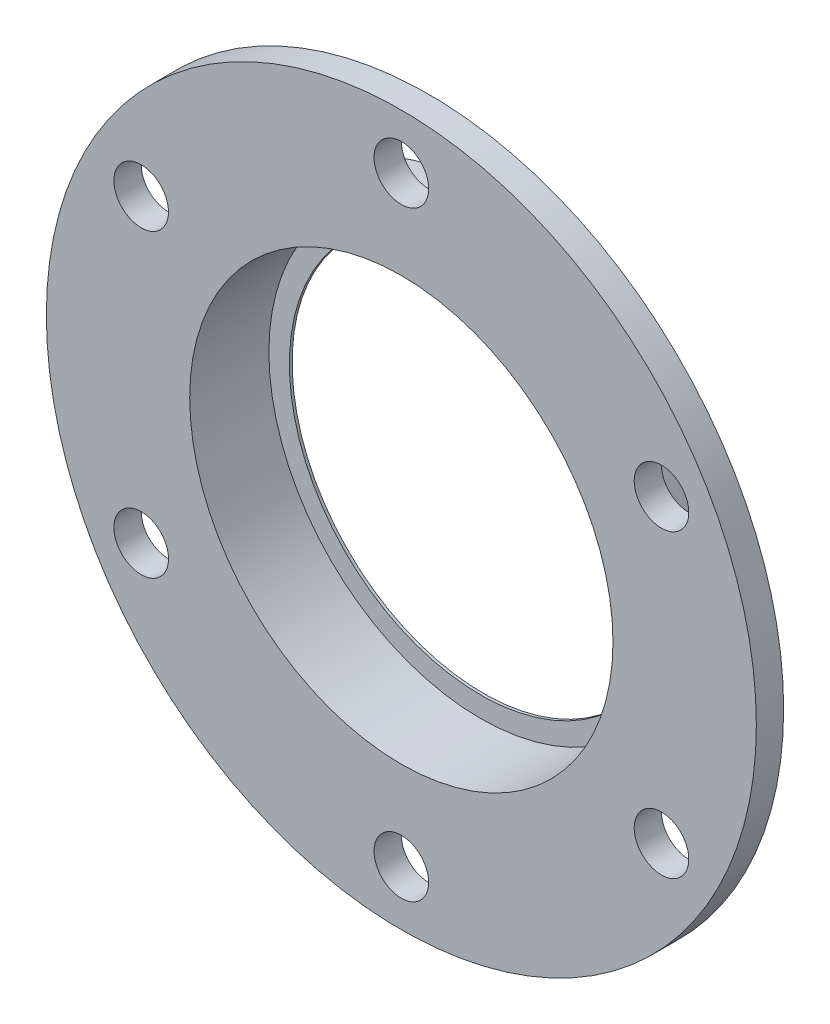
SolidWorks part; units mm, degrees
ref_plane "Front Plane" through (0, 0, 0) normal (0, 0, 1) x (1, 0, 0)
ref_plane "Top Plane" through (0, 0, 0) normal (0, 1, 0) x (1, 0, 0)
ref_plane "Right Plane" through (0, 0, 0) normal (1, 0, 0) x (0, 0, -1)
sketch "Sketch1" plane through (0, 0, 0) normal (0, 0, 1) x (1, 0, 0)
  circle A0 centre (0, 0) radius 45
  dimension "D1" = 90
extrude "Boss-Extrude1" add sketch "Sketch1" along normal blind 15
sketch "Sketch2" plane through (0, 0, 15) normal (0, 0, 1) x (1, 0, 0)
  circle A0 centre (0, 0) radius 38.75
  dimension "D1" = 77.5
extrude "Cut-Extrude1" cut sketch "Sketch2" against normal offset from surface (14.5 mm away) 0.5 up to face at (45, 0, 0)
sketch "Sketch3" plane through (0, 0, 0.5) normal (0, 0, 1) x (1, 0, 0)
  circle A0 centre (0, 0) radius 35
  dimension "D1" = 70
extrude "Cut-Extrude2" cut sketch "Sketch3" against normal through all
sketch "Sketch4" plane through (0, 0, 15) normal (0, 0, 1) x (1, 0, 0)
  circle A0 centre (0, 0) radius 65
  circle A1 centre (0, 0) radius 45
  circle A2 centre (0, 0) radius 45 construction
  dimension "D1" = 20
extrude "Boss-Extrude2" add sketch "Sketch4" against normal blind 5
sketch "Sketch5" plane through (0, 0, 10) normal (0, 0, -1) x (-1, 0, 0)
  circle A0 centre (0, 0) radius 55 construction
  circle A1 centre (0, 55) radius 5
  circle A2 centre (0, 0) radius 55 construction
  circle A3 centre (47.6314, 27.5) radius 5
  circle A4 centre (0, 0) radius 55 construction
  circle A5 centre (47.6314, -27.5) radius 5
  circle A6 centre (0, 0) radius 55 construction
  circle A7 centre (0, -55) radius 5
  circle A8 centre (0, 0) radius 55 construction
  circle A9 centre (-47.6314, -27.5) radius 5
  circle A10 centre (0, 0) radius 55 construction
  circle A11 centre (-47.6314, 27.5) radius 5
  point P23 (0, 0)
  dimension "D1" = 110
  dimension "D2" = 10
  dimension "D3" = 6
extrude "Cut-Extrude3" cut sketch "Sketch5" against normal through all
